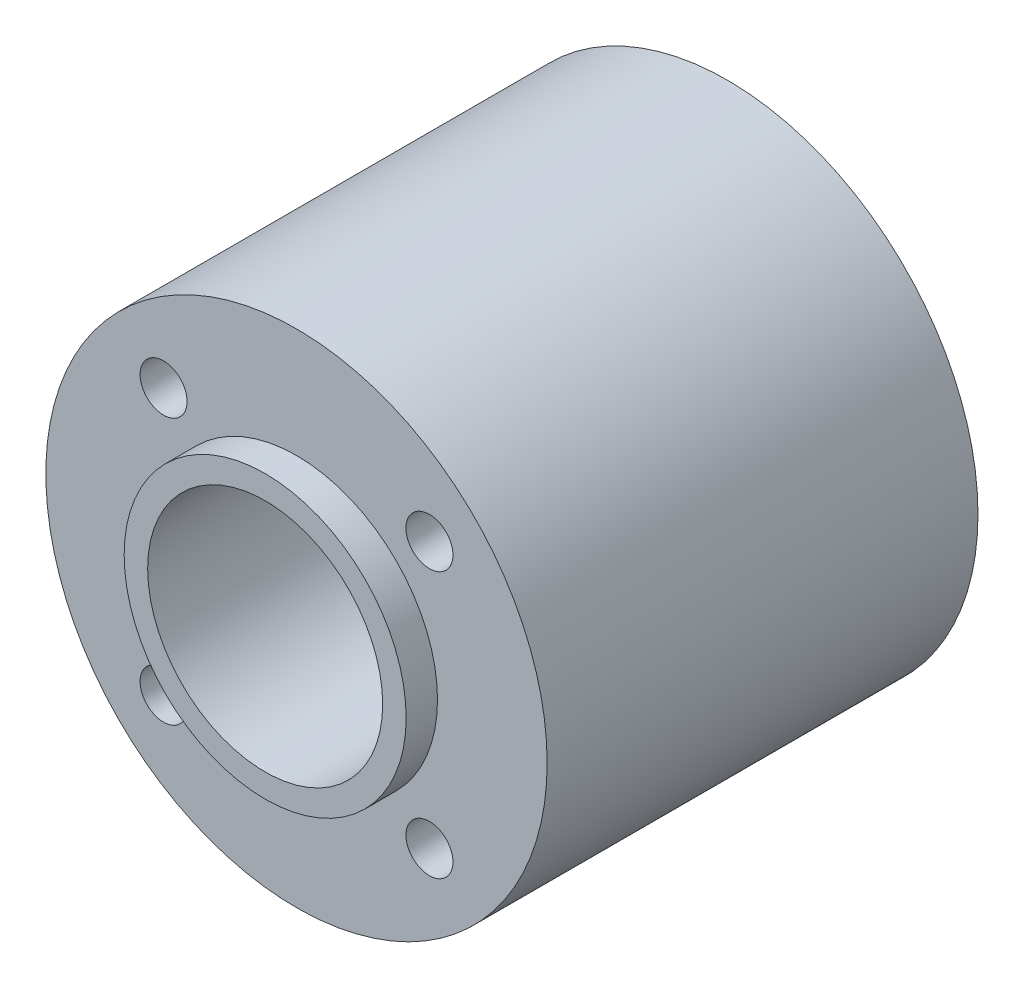
SolidWorks part; units mm, degrees
ref_plane "Front Plane" through (0, 0, 0) normal (0, 0, 1) x (1, 0, 0)
ref_plane "Top Plane" through (0, 0, 0) normal (0, 1, 0) x (1, 0, 0)
ref_plane "Right Plane" through (0, 0, 0) normal (1, 0, 0) x (0, 0, -1)
sketch "Sketch1" plane through (0, 0, 0) normal (0, 0, 1) x (1, 0, 0)
  line L0 (0, 0) -> (0, 25.1868) construction
  line L1 (0, 0) -> (-44.8671, 0) construction
  line L2 (0, 0) -> (-23.5667, 23.5667) construction
  circle A0 centre (0, 0) radius 7.5
  circle A1 centre (0, 0) radius 9
  circle A2 centre (0, 0) radius 12 construction
  circle A3 centre (0, 0) radius 16
  circle A4 centre (-8.4853, 8.4853) radius 1.5
  dimension "D1" = 32
  dimension "D2" = 24
  dimension "D3" = 18
  dimension "D4" = 15
  dimension "D6" = 3
  dimension "D5" = 45
extrude "Boss-Extrude1" add sketch "Sketch1" along normal mid plane 27.5 contours A3 A4 A1 | A4 | A1 A0
sketch "Sketch2" plane through (0, 0, 13.75) normal (0, 0, 1) x (1, 0, 0)
  circle A0 centre (-8.4853, 8.4853) radius 1.5 construction
  circle A1 centre (-8.4853, 8.4853) radius 1.5
extrude "Cut-Extrude1" cut sketch "Sketch2" against normal through all both and the other way through all
pattern_circular "CirPattern1" count 4 over 360 about axis through (0, 0, 0) along (0, 0, 1) of "Cut-Extrude1"
sketch "Sketch3" plane through (0, 0, 13.75) normal (0, 0, 1) x (1, 0, 0)
  circle A0 centre (0, 0) radius 7.5 construction
  circle A1 centre (0, 0) radius 7.5
  circle A2 centre (0, 0) radius 9 construction
  circle A3 centre (0, 0) radius 9
extrude "Boss-Extrude2" add sketch "Sketch3" along normal blind 2
mirror "Mirror1" about plane through (0, 0, 0) normal (0, 0, 1) of "Boss-Extrude2"
